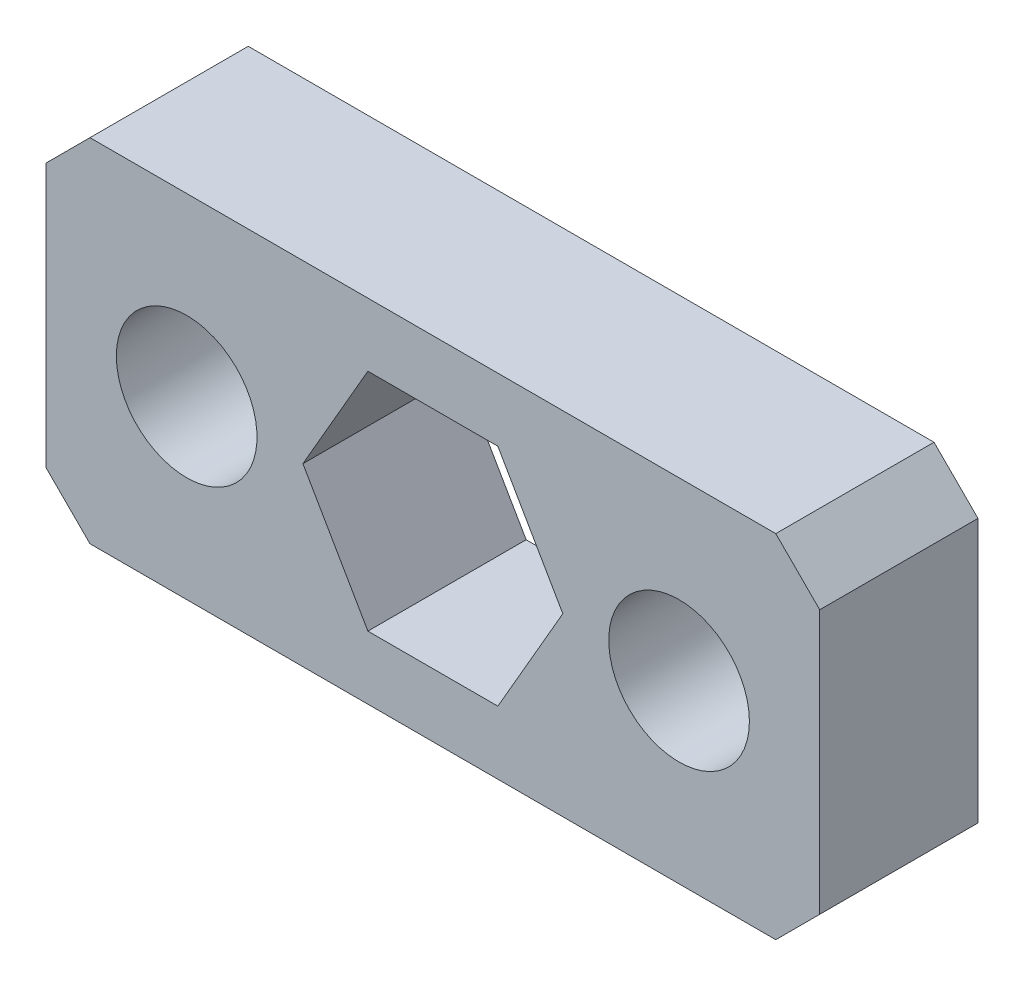
SolidWorks part; units mm, degrees
ref_plane "Front Plane" through (0, 0, 0) normal (0, 0, 1) x (1, 0, 0)
ref_plane "Top Plane" through (0, 0, 0) normal (0, 1, 0) x (1, 0, 0)
ref_plane "Right Plane" through (0, 0, 0) normal (1, 0, 0) x (0, 0, -1)
sketch "Model" plane through (0, 0, 0) normal (0, 0, 1) x (1, 0, 0)
  line L0 (0, 0) -> (0, 20) construction
  line L1 (-19.5, 20) -> (19.5, 20)
  line L2 (-22, 17.5) -> (-22, 2.5)
  line L3 (-19.5, 0) -> (19.5, 0)
  line L4 (22, 17.5) -> (22, 2.5)
  line L5 (-22, 10) -> (22, 10) construction
  line L6 (-22, 17.5) -> (-19.5, 20)
  line L7 (7.3901, 10) -> (3.695, 16.4)
  line L8 (3.695, 16.4) -> (-3.695, 16.4)
  line L9 (-3.695, 16.4) -> (-7.3901, 10)
  line L10 (-7.3901, 10) -> (-3.695, 3.6)
  line L11 (-3.695, 3.6) -> (3.695, 3.6)
  line L12 (3.695, 3.6) -> (7.3901, 10)
  line L13 (-19.5, 0) -> (-22, 2.5)
  line L14 (19.5, 20) -> (22, 17.5)
  line L15 (22, 2.5) -> (19.5, 0)
  circle A4 centre (14, 10) radius 4
  circle A5 centre (-14, 10) radius 4
  circle A6 centre (0, 10) radius 6.4 construction
  dimension "D4" = 8
  dimension "D2" = 20
  dimension "D3" = 44
  dimension "D5" = 12.8
  dimension "D6" = 14
  dimension "D1" = 2.5
  dimension "D8" = 2.5
  dimension "D7" = 2.5
extrude "Boss-Extrude1" add sketch "Model" along normal blind 9
equation "\"material-thickness\"= 9mm"
equation "\"linear-thread-nut-dia\"= 12.8mm ' Outer Diameter of the Nut used on the X Axis, typically M8 = 10mm"
equation "\"linear-bar-dia\"= 8mm ' Diameter of the metal slide bar used on the X Axis"
equation "\"D1@Boss-Extrude1\"=\"material-thickness\""
equation "\"D4@Model\"=\"linear-bar-dia\""
equation "\"D5@Model\"=\"linear-thread-nut-dia\""
